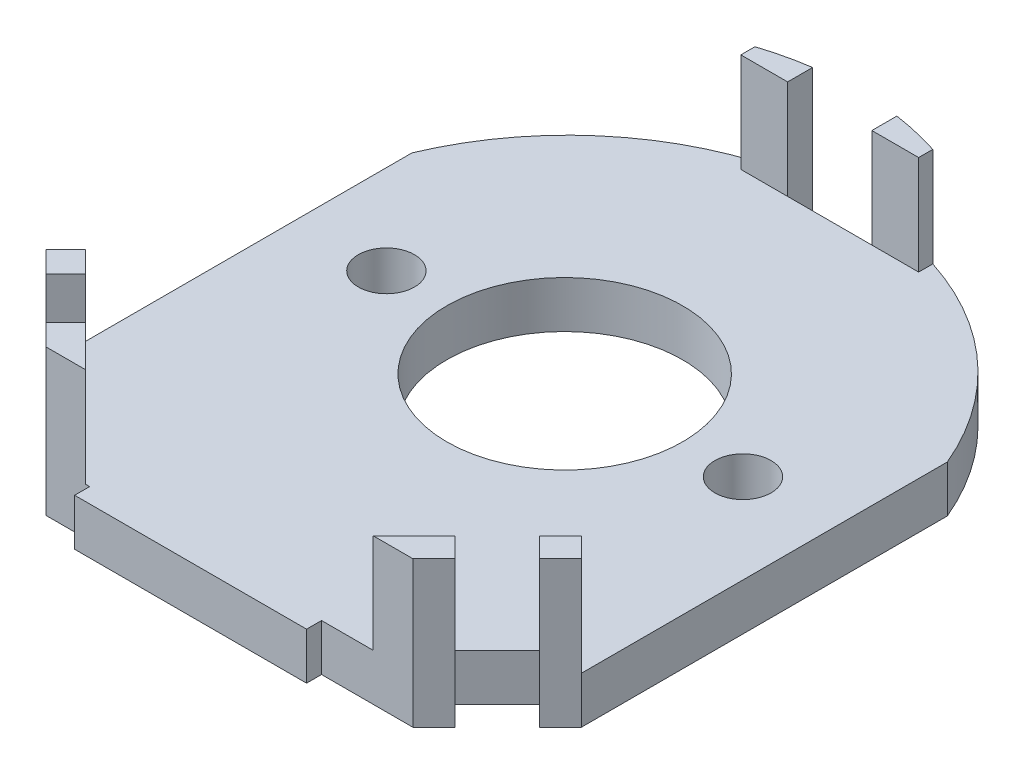
SolidWorks part; units mm, degrees
ref_plane "Front Plane" through (0, 0, 0) normal (0, 0, 1) x (1, 0, 0)
ref_plane "Top Plane" through (0, 0, 0) normal (0, 1, 0) x (1, 0, 0)
ref_plane "Right Plane" through (0, 0, 0) normal (1, 0, 0) x (0, 0, -1)
sketch "Sketch1" plane through (0, 0, 0) normal (0, 1, 0) x (1, 0, 0)
  line L0 (-25.7881, 0) -> (28.2246, 0) construction
  line L1 (0, 27.6131) -> (0, -42.9292) construction
  line L2 (-14.3, 6.14) -> (14.3, 6.14) construction
  line L3 (-14.3, 6.14) -> (-14.3, -13.41)
  line L4 (-9.8, -17.91) -> (-7.47, -17.91)
  line L5 (14.3, -13.41) -> (14.3, 6.14)
  line L6 (-14.3, -13.41) -> (-9.8, -17.91)
  line L7 (-7.47, -18.71) -> (4.92, -18.71)
  line L8 (-7.47, -18.71) -> (-7.47, -17.91)
  line L10 (4.92, -18.71) -> (4.92, -17.91)
  line L11 (-2.25, 14.16) -> (2.25, 14.16)
  line L12 (-2.25, 14.16) -> (-2.25, 15.4958)
  line L13 (4.92, -17.91) -> (9.8, -17.91)
  line L15 (2.25, 14.16) -> (2.25, 15.4958)
  line L16 (9.8, -17.91) -> (14.3, -13.41)
  arc A0 (14.3, 6.14) -> (2.25, 15.4958) centre (0, 0.16) ccw
  circle A1 centre (0, 0) radius 7.65 construction
  circle A3 centre (0, 0) radius 9.525 construction
  circle A4 centre (9.525, 0) radius 1.5
  circle A5 centre (-9.525, 0) radius 1.5
  circle A6 centre (0, 0) radius 6.3
  arc A7 (-2.25, 15.4958) -> (-14.3, 6.14) centre (0, 0.16) ccw
  circle A8 centre (0, 0.16) radius 15.5 construction
  point P10 (-14.3, -17.91)
  point P11 (14.3, -17.91)
  point P26 (0, 0)
  dimension "D1" = 31
  dimension "D2" = 0.16
  dimension "D3" = 28.6
  dimension "D4" = 15.3
  dimension "D9" = 19.05
  dimension "D10" = 3
  dimension "D11" = 12.6
  dimension "D5" = 17.91
  dimension "D6" = 6.83
  dimension "D7" = 12.39
  dimension "D8" = 0.8
  dimension "D12" = 14
  dimension "D13" = 4.5
extrude "Boss-Extrude1" add sketch "Sketch1" along normal blind 2.5
sketch "Sketch2" plane through (0, 2.5, 0) normal (0, 1, 0) x (1, 0, 0)
  line L0 (-12.1207, -13.468) -> (-9.858, -15.7307)
  line L1 (-12.05, -15.66) -> (-10.2536, -13.8636) construction
  line L2 (-14.3, -13.41) -> (-9.8, -17.91) construction
  line L3 (-12.1207, -13.468) -> (-13.1814, -14.5286)
  line L4 (-9.858, -15.7307) -> (-10.9186, -16.7914)
  line L5 (-13.1814, -14.5286) -> (-10.9186, -16.7914)
  line L6 (0, 0) -> (0, -19.3151) construction
  line L7 (12.1207, -13.468) -> (13.1814, -14.5286)
  line L8 (12.1207, -13.468) -> (9.858, -15.7307)
  line L9 (9.858, -15.7307) -> (10.9186, -16.7914)
  line L10 (13.1814, -14.5286) -> (10.9186, -16.7914)
  dimension "D1" = 3.2
  dimension "D2" = 1.5
extrude "Cut-Extrude1" cut sketch "Sketch2" against normal through all both and the other way through all
sketch "Sketch3" plane through (0, 2.5, 0) normal (0, 1, 0) x (1, 0, 0)
  line L0 (-13.1814, -14.5286) -> (-14.3, -13.41)
  line L1 (-14.3, -13.41) -> (-13.2393, -12.3493)
  line L2 (-13.2393, -12.3493) -> (-12.1207, -13.468)
  line L3 (-12.1207, -13.468) -> (-13.1814, -14.5286)
  line L4 (-10.9186, -16.7914) -> (-9.858, -15.7307)
  line L5 (-9.858, -15.7307) -> (-7.6787, -17.91)
  line L6 (-9.8, -17.91) -> (-7.47, -17.91) construction
  line L7 (-7.6787, -17.91) -> (-9.8, -17.91)
  line L8 (-9.8, -17.91) -> (-10.9186, -16.7914)
  line L9 (0, 17.1176) -> (0, -21.4639) construction
  line L10 (13.2393, -12.3493) -> (12.1207, -13.468)
  line L11 (14.3, -13.41) -> (13.2393, -12.3493)
  line L12 (13.1814, -14.5286) -> (14.3, -13.41)
  line L13 (12.1207, -13.468) -> (13.1814, -14.5286)
  line L14 (7.6787, -17.91) -> (9.8, -17.91)
  line L15 (9.858, -15.7307) -> (7.6787, -17.91)
  line L16 (10.9186, -16.7914) -> (9.858, -15.7307)
  line L17 (9.8, -17.91) -> (10.9186, -16.7914)
  line L18 (2.25, 15.4958) -> (2.25, 14.16)
  line L19 (2.25, 14.16) -> (4.75, 14.16)
  line L20 (-2.25, 15.4958) -> (-2.25, 14.16)
  line L21 (-2.25, 14.16) -> (-4.75, 14.16)
  line L22 (4.75, 14.16) -> (4.75, 14.9142)
  line L23 (-4.75, 14.16) -> (-4.75, 14.9142)
  arc A0 (4.75, 14.9142) -> (2.25, 15.4958) centre (0, 0.16) ccw
  arc A1 (-2.25, 15.4958) -> (-4.75, 14.9142) centre (0, 0.16) ccw
  dimension "D1" = 2.5
extrude "Boss-Extrude2" add sketch "Sketch3" along normal blind 5.3
